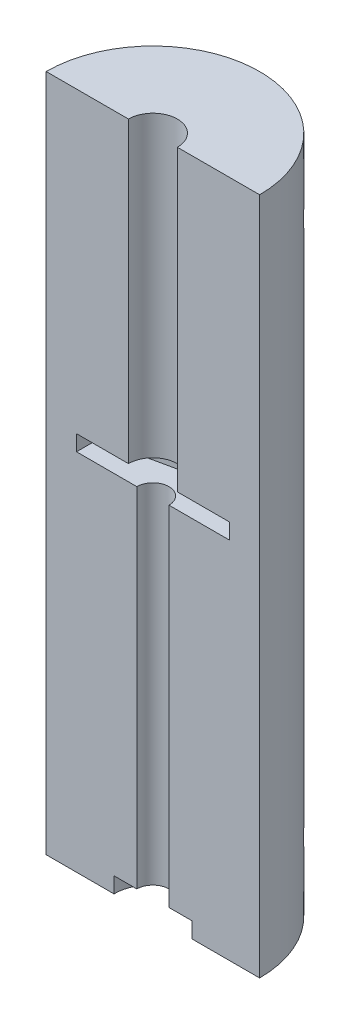
SolidWorks part; units mm, degrees
ref_plane "Front Plane" through (0, 0, 0) normal (0, 0, 1) x (1, 0, 0)
ref_plane "Top Plane" through (0, 0, 0) normal (0, 1, 0) x (1, 0, 0)
ref_plane "Right Plane" through (0, 0, 0) normal (1, 0, 0) x (0, 0, -1)
sketch "Sketch1" plane through (0, 0, 0) normal (0, 1, 0) x (1, 0, 0)
  line L0 (0, 0) -> (29.9, 0)
  arc A0 (0, 0) -> (29.9, 0) centre (14.95, 0) cw
  dimension "D1" = 29.9
extrude "Boss-Extrude1" add sketch "Sketch1" along normal blind 95 contours A0 L0
sketch "Sketch3" plane through (0, 0, 0) normal (0, 0, 1) x (1, 0, 0)
  line L0 (14.95, 0) -> (14.95, 95)
  line L1 (0, 0) -> (29.9, 0) construction
  line L2 (0, 95) -> (29.9, 95) construction
  line L3 (9.7, 0) -> (20.2, 0)
  line L4 (9.7, 0) -> (9.7, 2.2)
  line L7 (12.8, 2.2) -> (9.7, 2.2)
  line L8 (12.8, 2.2) -> (12.8, 51)
  line L9 (12.8, 51) -> (3.05, 51)
  line L10 (3.05, 51) -> (3.05, 53.2)
  line L11 (11.45, 53.2) -> (11.45, 95)
  line L12 (3.05, 53.2) -> (11.45, 53.2)
  line L13 (20.2, 0) -> (20.2, 2.2)
  line L14 (17.1, 2.2) -> (20.2, 2.2)
  line L15 (17.1, 2.2) -> (17.1, 51)
  line L16 (17.1, 51) -> (26.85, 51)
  line L17 (26.85, 51) -> (26.85, 53.2)
  line L18 (26.85, 53.2) -> (18.45, 53.2)
  line L19 (18.45, 53.2) -> (18.45, 95)
  point P9 (14.95, 0)
  dimension "D1" = 10.5
  dimension "D2" = 2.2
  dimension "D3" = 48.8
  dimension "D4" = 2.2
  dimension "D5" = 9.75
  dimension "D6" = 2.15
  dimension "D7" = 3.5
sketch "Sketch4" plane through (0, 0, 0) normal (0, 1, 0) x (1, 0, 0)
  line L0 (20.4, 0) -> (9.5, 0)
  line L1 (9.7, 0) -> (20.2, 0) construction
  line L2 (12.8, 0) -> (9.7, 0) construction
  arc A0 (9.5, 0) -> (20.4, 0) centre (14.95, 0) cw
  point P7 (14.95, 0)
  dimension "D1" = 10.9
extrude "Cut-Extrude1" cut sketch "Sketch4" along normal blind 2.2
ref_plane "Plane1" through (0, 2.2, 0) normal (0, -1, 0) x (-1, 0, 0)
sketch "Sketch5" plane through (0, 2.2, 0) normal (0, -1, 0) x (-1, 0, 0)
  line L0 (-17.2, 0) -> (-12.7, 0)
  line L1 (-9.7, 0) -> (-20.2, 0) construction
  line L2 (-12.8, 0) -> (-3.05, 0) construction
  circle A0 centre (-14.95, 0) radius 2.25
  point P8 (-14.95, 0)
  dimension "D1" = 4.5
extrude "Cut-Extrude2" cut sketch "Sketch5" against normal blind 48.8 contours L0 A0
ref_plane "Plane2" through (0, 51, 0) normal (0, 1, 0) x (1, 0, 0)
sketch "Sketch6" plane through (0, 51, 0) normal (0, 1, 0) x (1, 0, 0)
  line L0 (25.65, 0) -> (4.25, 0)
  line L1 (3.05, 0) -> (11.45, 0) construction
  line L2 (12.8, 0) -> (3.05, 0) construction
  line L4 (4.25, 0) -> (4.25, 3)
  line L5 (4.25, 3) -> (14.95, 5.3)
  line L6 (25.65, 0) -> (25.65, 3)
  line L7 (25.65, 3) -> (14.95, 5.3)
  dimension "D3" = 3
  dimension "D4" = 3
  dimension "D5" = 5.3
extrude "Cut-Extrude3" cut sketch "Sketch6" along normal blind 2.2
ref_plane "Plane4" through (0, 53.2, 0) normal (0, -1, 0) x (-1, 0, 0)
sketch "Sketch8" plane through (0, 53.2, 0) normal (0, -1, 0) x (-1, 0, 0)
  line L0 (-14.95, 0) -> (-18.45, 0)
  circle A1 centre (-14.95, 0) radius 3.425
  dimension "D1" = 6.85
extrude "Cut-Extrude4" cut sketch "Sketch8" against normal blind 50
sketch "Sketch9" plane through (0, 0, 0) normal (0, 0, 1) x (1, 0, 0)
  line L3 (11.525, 95) -> (0, 95)
  circle A0 centre (5.375, 85) radius 1.5
  circle A1 centre (5.375, 10) radius 1.5
  circle A2 centre (23.125, 10) radius 1.5
  circle A3 centre (23.125, 85) radius 1.5
  dimension "D2" = 3
  dimension "D4" = 3
ref_plane "Plane5" through (0, 0, -0.8) normal (0, 0, 1) x (1, 0, 0)
fillet "Fillet1" radius 1 3 edges at (4.25, 52.1, -3) (14.95, 52.1, -5.3) (25.65, 52.1, -3)
sketch "Sketch11" plane through (0, 0, -0.8) normal (0, 0, 1) x (1, 0, 0)
  circle A0 centre (5.375, 85) radius 3
  circle A1 centre (23.125, 85) radius 3
  circle A2 centre (5.375, 10) radius 3
  circle A3 centre (23.125, 10) radius 3
  dimension "D1" = 6
  dimension "D2" = 6
  dimension "D3" = 6
  dimension "D4" = 6
extrude "Cut-Extrude5" cut sketch "Sketch11" against normal blind 15
